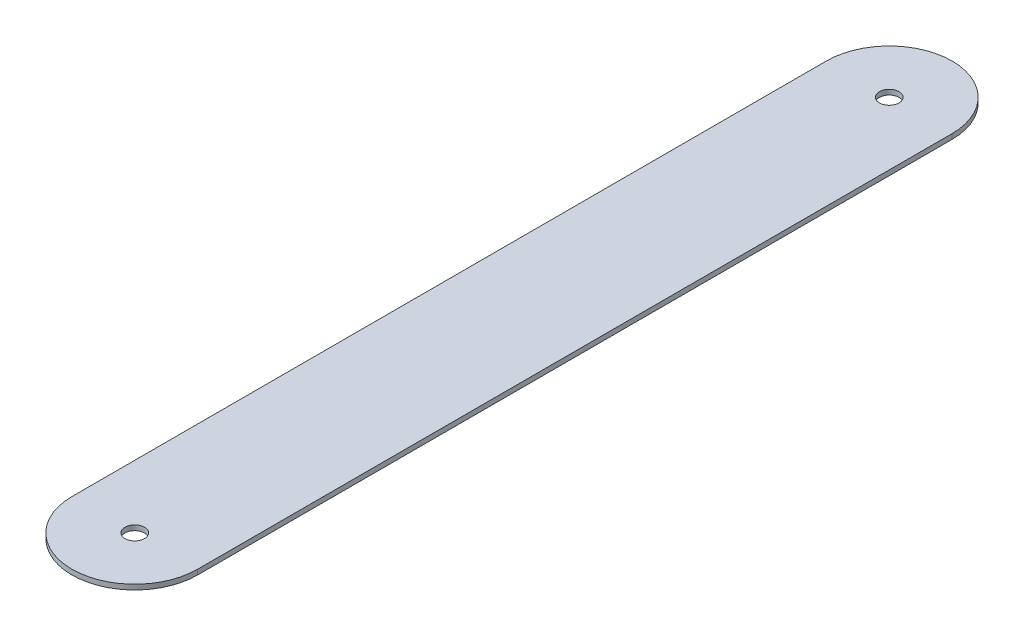
SolidWorks part; units mm, degrees
ref_plane "Front Plane" through (0, 0, 0) normal (0, 0, 1) x (1, 0, 0)
ref_plane "Top Plane" through (0, 0, 0) normal (0, 1, 0) x (1, 0, 0)
ref_plane "Right Plane" through (0, 0, 0) normal (1, 0, 0) x (0, 0, -1)
sketch "Sketch1" plane through (0, 0, 0) normal (0, 1, 0) x (1, 0, 0)
  line L0 (0, 0) -> (0, 150) construction
  line L1 (0, 0) -> (0, 150) construction
  line L4 (-12.5, 0) -> (-12.5, 150)
  line L5 (12.5, 0) -> (12.5, 150)
  line L6 (0, 0) -> (53.3311, 0) construction
  circle A4 centre (0, 0) radius 1.95
  circle A5 centre (0, 150) radius 1.95
  arc A6 (-12.5, 0) -> (12.5, 0) centre (0, 0) ccw
  arc A7 (12.5, 150) -> (-12.5, 150) centre (0, 150) ccw
  point P6 (0, 75)
  dimension "D3" = 150
  dimension "D4" = 3.9
  dimension "D1" = 25
  dimension "D2" = 90
extrude "Boss-Extrude1" add sketch "Sketch1" along normal blind 1
